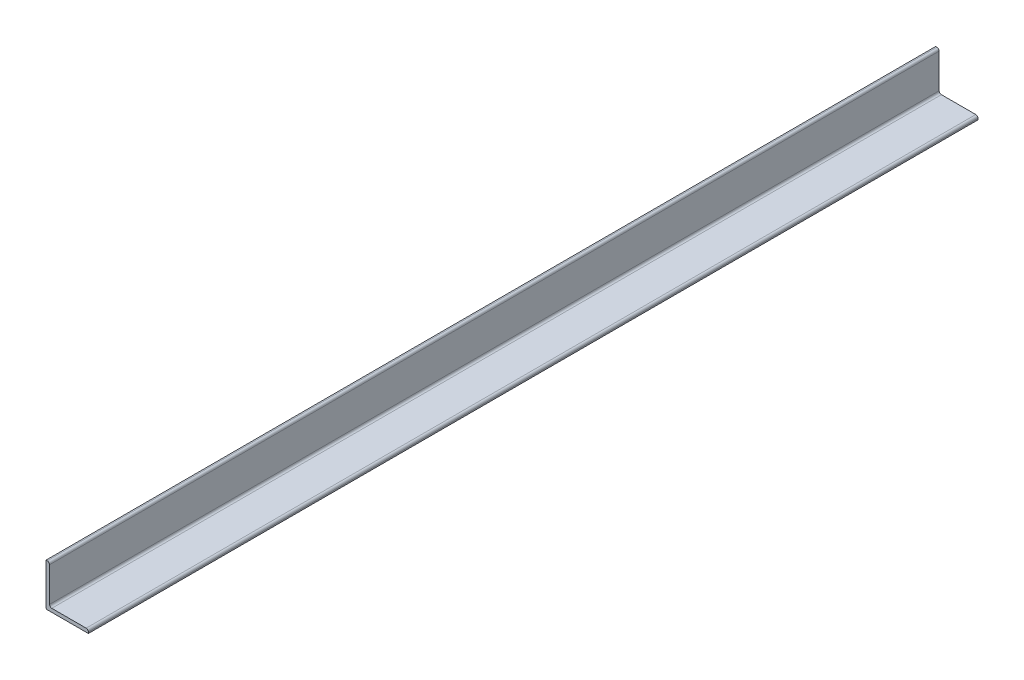
SolidWorks part; units mm, degrees
ref_plane "Front Plane" through (0, 0, 0) normal (0, 0, 1) x (1, 0, 0)
ref_plane "Top Plane" through (0, 0, 0) normal (0, 1, 0) x (1, 0, 0)
ref_plane "Right Plane" through (0, 0, 0) normal (1, 0, 0) x (0, 0, -1)
sketch "Sketch1" plane through (0, 0, 0) normal (0, 0, 1) x (1, 0, 0)
  line L0 (0, 0) -> (0, 19.05)
  line L1 (0, 19.05) -> (1.5875, 19.05)
  line L2 (1.5875, 19.05) -> (1.5875, 1.5875)
  line L3 (1.5875, 1.5875) -> (19.05, 1.5875)
  line L4 (19.05, 1.5875) -> (19.05, 0)
  line L5 (19.05, 0) -> (0, 0)
  dimension "D1" = 1.5875
  dimension "D2" = 19.05
extrude "Boss-Extrude1" add sketch "Sketch1" along normal blind 400
fillet "Fillet1" radius 1 3 edges at (19.05, 1.5875, 200) (1.5875, 1.5875, 200) (1.5875, 19.05, 200)
fillet "Fillet2" radius 0.5 1 edges at (0, 0, 200)
ref_plane "Plane1" through (0, 0, 200) normal (0, 0, 1) x (1, 0, 0)
